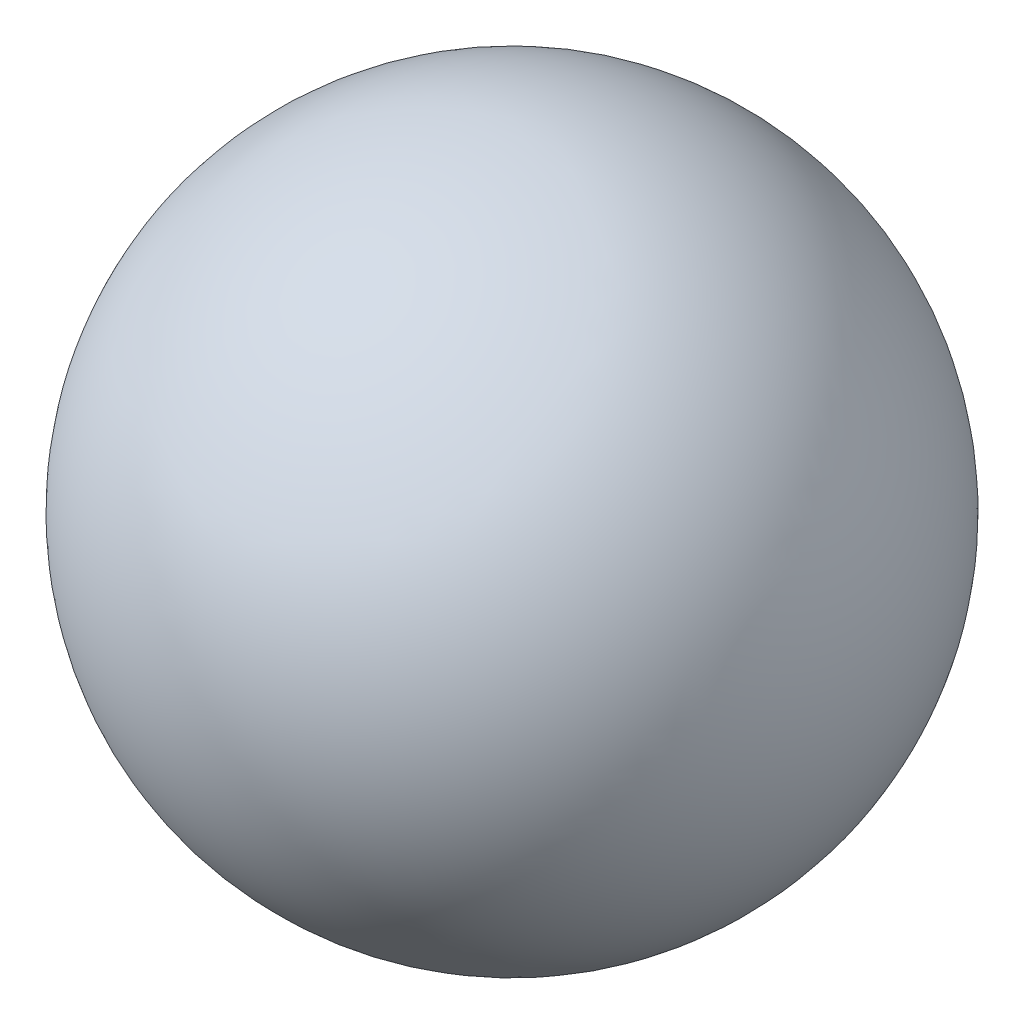
SolidWorks part; units mm, degrees
ref_plane "Front Plane" through (0, 0, 0) normal (0, 0, 1) x (1, 0, 0)
ref_plane "Top Plane" through (0, 0, 0) normal (0, 1, 0) x (1, 0, 0)
ref_plane "Right Plane" through (0, 0, 0) normal (1, 0, 0) x (0, 0, -1)
sketch "Sketch2" plane through (0, 0, 0) normal (0, 1, 0) x (1, 0, 0)
  line L0 (-5.75, 0) -> (5.75, 0)
  arc A0 (5.75, 0) -> (-5.75, 0) centre (0, 0) ccw
  dimension "D1" = 11.5
revolve "Revolve4" add sketch "Sketch2" angle 360 about L0
